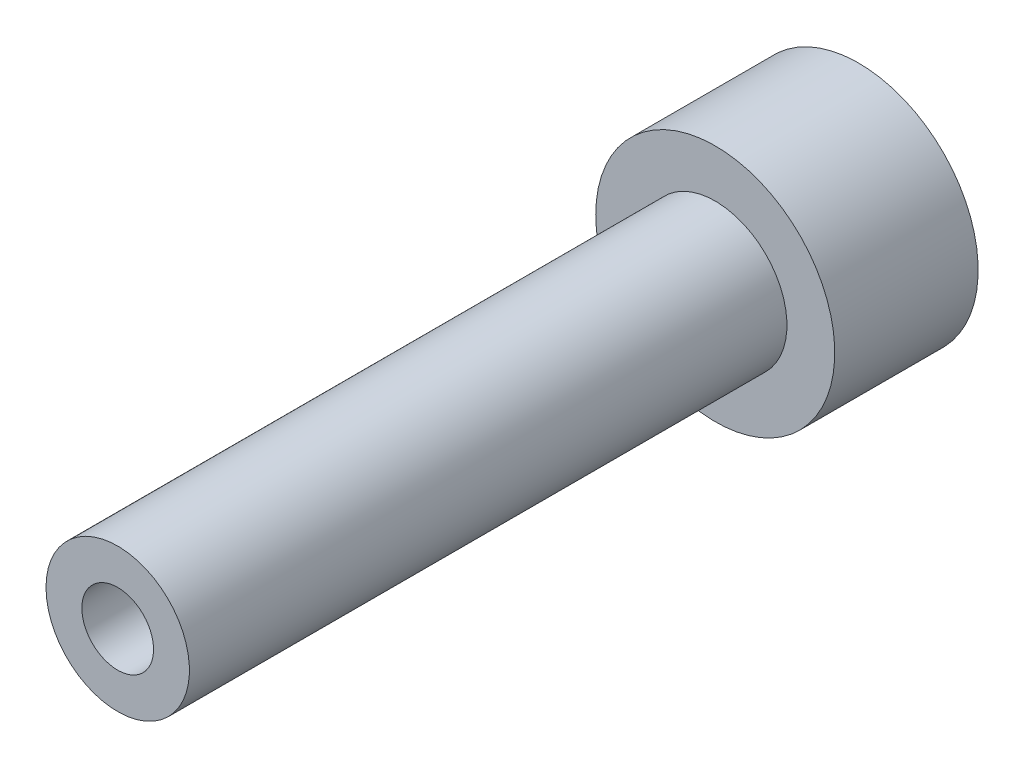
SolidWorks part; units mm, degrees
material "Brass"
ref_plane "Front Plane" through (0, 0, 0) normal (0, 0, 1) x (1, 0, 0)
ref_plane "Top Plane" through (0, 0, 0) normal (0, 1, 0) x (1, 0, 0)
ref_plane "Right Plane" through (0, 0, 0) normal (1, 0, 0) x (0, 0, -1)
sketch "Sketch1" plane through (0, 0, 0) normal (1, 0, 0) x (0, 0, -1)
  line L0 (0, 0) -> (-54.3302, 0) construction
  line L1 (0, 0.85) -> (0, 2.5)
  line L2 (0, 2.5) -> (-3, 2.5)
  line L3 (-3, 2.5) -> (-3, 1.5)
  line L4 (-3, 1.5) -> (-15.5, 1.5)
  line L5 (-15.5, 1.5) -> (-15.5, 0.75)
  line L6 (-15.5, 0.75) -> (-2, 0.75)
  line L7 (-2, 0.75) -> (-2, 0.85)
  line L8 (-2, 0.85) -> (0, 0.85)
  dimension "D1" = 1.5
  dimension "D2" = 3
  dimension "D3" = 5
  dimension "D4" = 1.7
  dimension "D5" = 2
  dimension "D6" = 3
  dimension "D7" = 15.5
revolve "Revolve1" add sketch "Sketch1" angle 360 about L0
cosmetic thread "Cosmetic Thread1" parameters "D1"=5, "D2"=2.439
